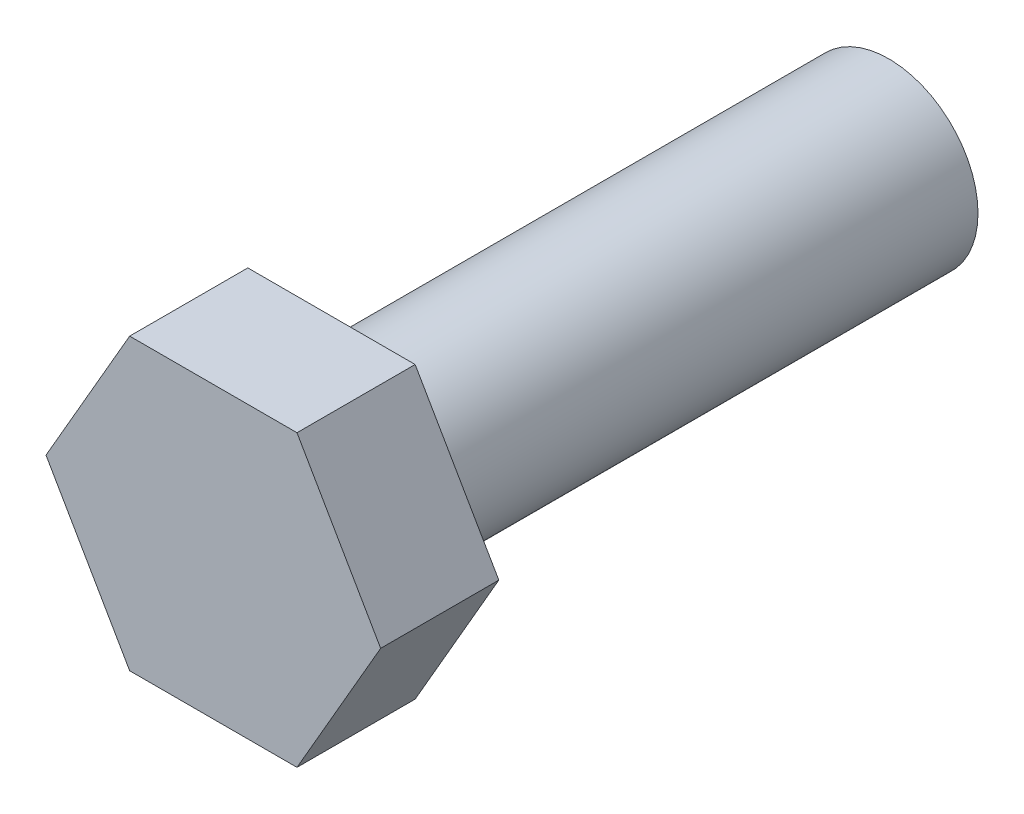
SolidWorks part; units mm, degrees
material "AISI 304"
ref_plane "Front Plane" through (0, 0, 0) normal (0, 0, 1) x (1, 0, 0)
ref_plane "Top Plane" through (0, 0, 0) normal (0, 1, 0) x (1, 0, 0)
ref_plane "Right Plane" through (0, 0, 0) normal (1, 0, 0) x (0, 0, -1)
sketch "Sketch1" plane through (0, 0, 0) normal (0, 0, 1) x (1, 0, 0)
  circle A0 centre (0, 0) radius 4
  dimension "D1" = 8
extrude "Extrude1" add sketch "Sketch1" against normal blind 25
cosmetic thread "Cosmetic Thread1" parameters "D1"=25, "D2"=6.8
sketch "Sketch2" plane through (0, 0, 0) normal (0, 0, 1) x (1, 0, 0)
  line L1 (-3.7528, 6.5) -> (-7.5056, 0)
  line L2 (-7.5056, 0) -> (-3.7528, -6.5)
  line L3 (-3.7528, -6.5) -> (3.7528, -6.5)
  line L4 (3.7528, -6.5) -> (7.5056, 0)
  line L5 (7.5056, 0) -> (3.7528, 6.5)
  line L6 (3.7528, 6.5) -> (-3.7528, 6.5)
  circle A0 centre (0, 0) radius 6.5 construction
  dimension "D1" = 13
extrude "Extrude2" add sketch "Sketch2" along normal blind 5.3
